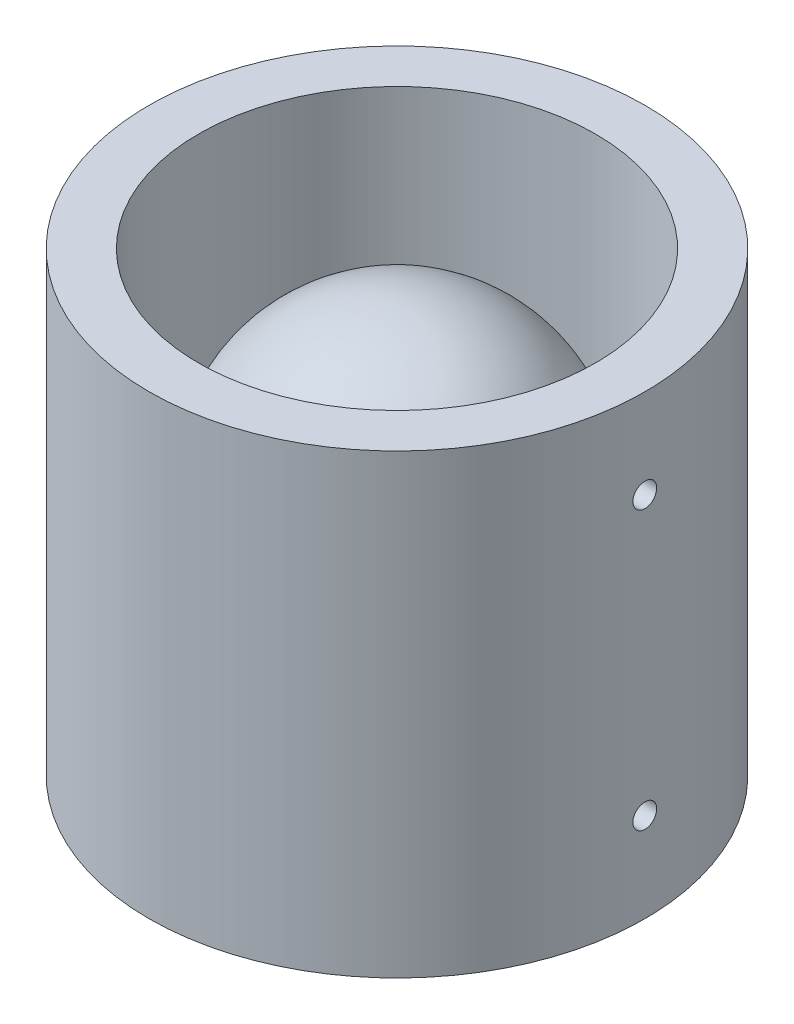
SolidWorks part; units mm, degrees
ref_plane "Front Plane" through (0, 0, 0) normal (0, 0, 1) x (1, 0, 0)
ref_plane "Top Plane" through (0, 0, 0) normal (0, 1, 0) x (1, 0, 0)
ref_plane "Right Plane" through (0, 0, 0) normal (1, 0, 0) x (0, 0, -1)
sketch "Sketch1" plane through (0, 0, 0) normal (0, 0, 1) x (1, 0, 0)
  line L0 (0, 0) -> (0, 24.8092) construction
  line L1 (8, 12.5) -> (8, 18.9472) construction
  line L2 (12.5, 0) -> (10, 0)
  line L3 (12.5, 0) -> (12.5, 23)
  line L4 (12.5, 23) -> (10, 23)
  line L5 (10, 0) -> (10, 23)
  line L6 (10, 12.5) -> (8, 12.5)
  line L7 (10, 12.5) -> (10, 11.5)
  line L8 (10, 11.5) -> (8, 11.5)
  line L9 (8, 12.5) -> (8, 11.5)
  line L10 (8, 11.5) -> (6.8, 11.5)
  line L11 (0, 20.5) -> (0, 18.9)
  line L12 (6.8, 11.5) -> (7.2618, 16.9547) construction
  arc A0 (0, 20.5) -> (8, 12.5) centre (0, 12.5) cw
  arc A1 (0, 18.9) -> (6.8, 11.5) centre (0, 12.0757) cw
  dimension "D1" = 10
  dimension "D2" = 2.5
  dimension "D3" = 23
  dimension "D4" = 1
  dimension "D5" = 2
  dimension "D6" = 1.6
  dimension "D7" = 90
  dimension "D8" = 1.2
  dimension "D9" = 11.5
revolve "Revolve1" add sketch "Sketch1" angle 360 about L0
ref_plane "Plane1" through (12.5, 0, 0) normal (1, 0, 0) x (0, 0, -1)
sketch "Sketch2" plane through (12.5, 0, 0) normal (1, 0, 0) x (0, 0, -1)
  line L0 (0, 0) -> (0, 23) construction
  line L1 (0, 0) -> (0, 23)
  circle A0 centre (0, 18.5) radius 0.6
  circle A1 centre (0, 4.5) radius 0.6
  dimension "D3" = 1.2
  dimension "D1" = 4.5
  dimension "D2" = 4.5
  dimension "D4" = 14
extrude "Cut-Extrude1" cut sketch "Sketch2" against normal up to next contours L1 A0 | L1 A0 | L1 A1 | L1 A1
